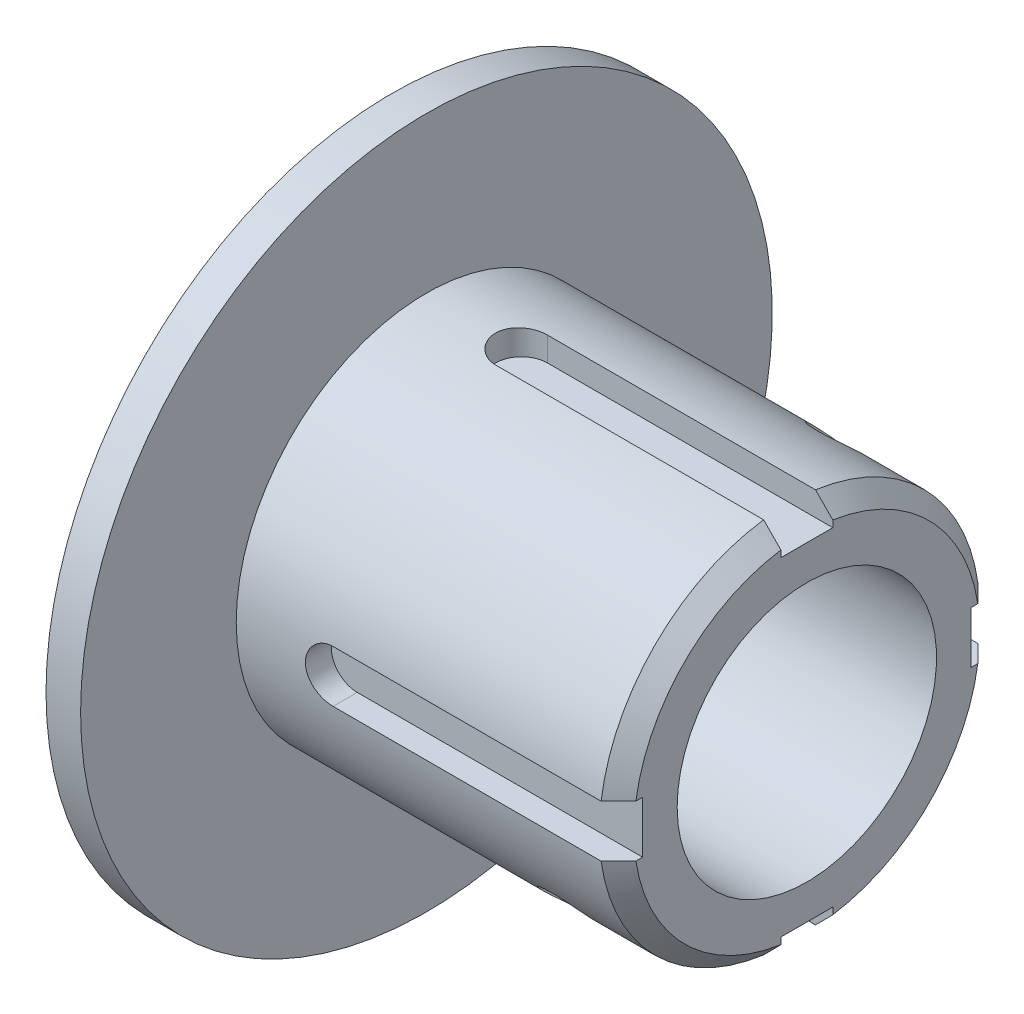
SolidWorks part; units mm, degrees
ref_plane "Plan1" through (0, 0, 0) normal (0, 0, 1) x (1, 0, 0)
ref_plane "Plan2" through (0, 0, 0) normal (0, 1, 0) x (1, 0, 0)
ref_plane "Plan3" through (0, 0, 0) normal (1, 0, 0) x (0, 0, -1)
sketch "Esquisse1" plane through (0, 0, 0) normal (0, 0, 1) x (1, 0, 0)
  line L0 (0, 40) -> (-4, 40)
  line L1 (-4, 40) -> (-10, 23.5151)
  line L2 (-10, 23.5151) -> (-10, 15)
  line L3 (0, 40) -> (0, 22)
  line L4 (0, 22) -> (42, 22)
  line L5 (42, 22) -> (44, 20)
  line L6 (44, 20) -> (44, 15)
  line L7 (44, 15) -> (-10, 15)
  line L8 (0, 0) -> (55, 0) construction
  dimension "D1" = 40
  dimension "D2" = 4
  dimension "D3" = 22
  dimension "D4" = 15
  dimension "D5" = 2
  dimension "D6" = 45
  dimension "D7" = 44
  dimension "D8" = 10
  dimension "D9" = 20
revolve "Base-Révolution" add sketch "Esquisse1" angle 360 about L8
ref_plane "Plan4" through (21, 22, 0) normal (0, 1, 0) x (0, 0, -1)
sketch "Esquisse3" plane through (21, 22, 0) normal (0, 1, 0) x (0, 0, -1)
  line L0 (-20, -23) -> (20, -23) construction
  line L1 (-3, -25) -> (3, -25)
  line L2 (-3, -25) -> (-3, 10)
  line L4 (3, -25) -> (3, 10)
  arc A0 (3, 10) -> (-3, 10) centre (0, 10) ccw
  dimension "D1" = 6
  dimension "D2" = 2
extrude "Enlèv. mat.-Extru.1" cut sketch "Esquisse3" against normal blind 3
pattern_circular "Répétition circulaire1" count 4 every 90 about axis through (0, 0, 0) along (1, 0, 0)
ref_plane "Plan5" through (0, 0, 0) normal (0, -0.7071, 0.7071) x (1, 0, 0)
sketch "Esquisse5" plane through (0, 0, 0) normal (0, -0.7071, 0.7071) x (1, 0, 0)
  line L0 (0, 0) -> (55, 0) construction
  line L1 (44, -11.8608) -> (44, 11.8608) construction
  circle A0 centre (32, 0) radius 3
  dimension "D1" = 6
  dimension "D2" = 12
extrude "Enlèv. mat.-Extru.2" cut sketch "Esquisse5" against normal mid plane 80
